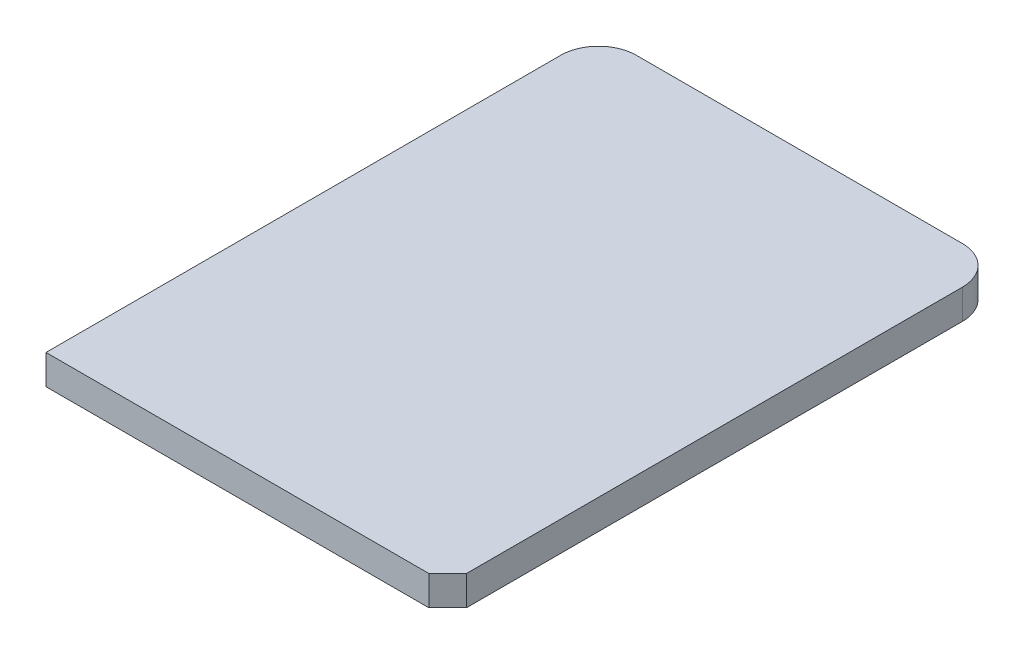
SolidWorks part; units mm, degrees
ref_plane "Front Plane" through (0, 0, 0) normal (0, 0, 1) x (1, 0, 0)
ref_plane "Top Plane" through (0, 0, 0) normal (0, 1, 0) x (1, 0, 0)
ref_plane "Right Plane" through (0, 0, 0) normal (1, 0, 0) x (0, 0, -1)
sketch "Sketch2" plane through (0, 0, 0) normal (0, 1, 0) x (1, 0, 0)
  line L0 (0, 2) -> (0, 0)
  line L1 (2, 0) -> (20.3, 0)
  line L2 (0, 2) -> (0, 27.3)
  line L3 (2, 29.3) -> (19.3, 29.3)
  line L4 (21.3, 1) -> (21.3, 27.3)
  line L5 (0, 0) -> (2, 0)
  line L6 (20.3, 0) -> (21.3, 1)
  arc A1 (0, 27.3) -> (2, 29.3) centre (2, 27.3) cw
  arc A2 (19.3, 29.3) -> (21.3, 27.3) centre (19.3, 27.3) cw
  point P6 (21.3, 0)
  point P7 (21.3, 0)
  point P10 (0, 29.3)
  point P13 (21.3, 29.3)
  point P16 (0, 0)
  dimension "D4" = 2
  dimension "D5" = 2
  dimension "D1" = 21.3
  dimension "D2" = 29.3
extrude "Boss-Extrude2" add sketch "Sketch2" along normal blind 1.575
hole_wizard "M3 Clearance Hole1" [suppressed] positions "Sketch3" profile "Sketch4" hole size "M3" standard "ISO"
sketch "Sketch3" [suppressed] plane through (-4.6487, 1.575, 19.1681) normal (0, 1, 0) x (-1, 0, 0)
  point P0 (-23.5587, -42.7243)
  point P1 (-23.5587, -67.2443)
  point P2 (-7.0387, -67.2443)
  point P3 (-7.0387, -42.7243)
sketch "Sketch4" [suppressed] plane through (18.91, 1.575, -23.5562) normal (1, 0, 0) x (0, 0, 1)
  line L0 (0, 0) -> (0, 1.575)
  line L1 (0, 1.575) -> (1.6, 1.575)
  line L2 (1.6, 1.575) -> (1.6, 0)
  line L3 (1.6, 0) -> (0, 0)
  line L4 (0, -6.35) -> (0, 107.95) construction
  dimension "Thru Hole Dia." = 3.2
  dimension "Thru Hole Depth" = 1.575
equation "\"M1PCB_side\"= 10mm"
equation "\"ODRM_TC203\"= 10.650mm"
equation "\"IDRM_TC203\"= 5.5mm"
equation "\"HTM_TC203\"= 7.620mm"
equation "\"D1@Sketch2\"=\"ODRM_TC203\"*2"
equation "\"D2@Sketch2\"=(\"ODRM_TC203\"*2)+8mm"
